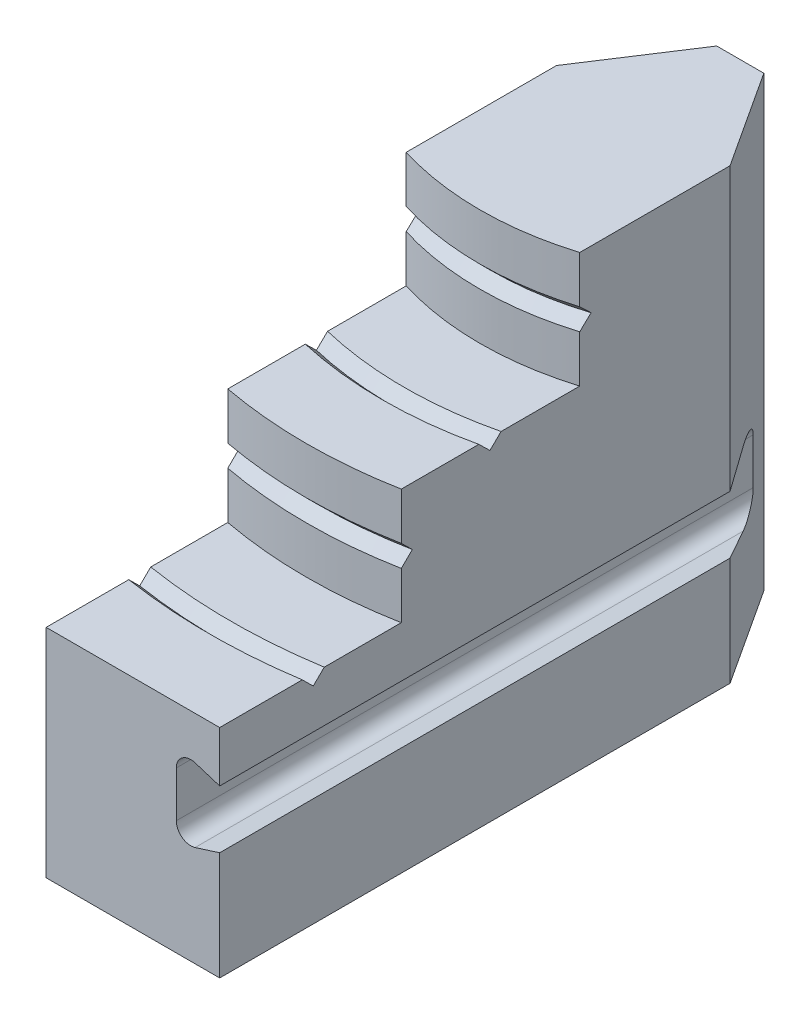
SolidWorks part; units mm, degrees
ref_plane "Front Plane" through (0, 0, 0) normal (0, 0, 1) x (1, 0, 0)
ref_plane "Top Plane" through (0, 0, 0) normal (0, 1, 0) x (1, 0, 0)
ref_plane "Right Plane" through (0, 0, 0) normal (1, 0, 0) x (0, 0, -1)
sketch "Sketch1" plane through (0, 0, 0) normal (0, 1, 0) x (1, 0, 0)
  line L0 (0, 0) -> (0, 89) construction
  line L1 (-12, 0) -> (12, 0)
  line L2 (-12, 0) -> (-12, 70.5832)
  line L3 (-3.2579, 84) -> (3.2579, 84)
  line L4 (12, 0) -> (12, 70.5832)
  line L5 (-3.2579, 84) -> (-12, 70.5832)
  line L6 (3.2579, 84) -> (12, 70.5832)
  line L7 (0, 89) -> (-3.2579, 84) construction
  line L8 (0, 89) -> (3.2579, 84) construction
  line L9 (-12, 70.5832) -> (-12, 84) construction
  line L10 (-12, 84) -> (-3.2579, 84) construction
  line L11 (12, 70.5832) -> (12, 84) construction
  line L12 (3.2579, 84) -> (12, 84) construction
  point P5 (0, 0)
  dimension "D1" = 24
  dimension "D2" = 89
  dimension "D3" = 84
  dimension "D4" = 33.087
extrude "Boss-Extrude1" add sketch "Sketch1" along normal blind 62
sketch "Sketch2" plane through (0, 0, 0) normal (1, 0, 0) x (0, 0, -1)
  line L0 (89, 0) -> (89, 113.7823) construction
  line L1 (89, 0) -> (84, 0) construction
  line L2 (0, 0) -> (89, 0) construction
  line L5 (48, 55.5) -> (49.5, 54)
  line L6 (-12, 30) -> (10.5, 30)
  line L7 (24, 30) -> (24, 36.5)
  line L8 (24, 46) -> (34.5, 46)
  line L9 (48, 46) -> (48, 52.5)
  line L10 (49.5, 54) -> (48, 52.5)
  line L13 (34.5, 46) -> (36, 44.5)
  line L15 (-12, 30) -> (-12, 70)
  line L16 (-12, 70) -> (48, 70)
  line L18 (0, 62) -> (0, 0) construction
  line L19 (0, 62) -> (70.5832, 62) construction
  line L20 (36, 44.5) -> (37.5, 46)
  line L21 (24, 39.5) -> (25.5, 38)
  line L22 (25.5, 38) -> (24, 36.5)
  line L23 (10.5, 30) -> (12, 28.5)
  line L24 (12, 28.5) -> (13.5, 30)
  line L25 (48, 52.5) -> (48, 55.5) construction
  line L26 (48, 55.5) -> (48, 70)
  line L27 (34.5, 46) -> (37.5, 46) construction
  line L28 (37.5, 46) -> (48, 46)
  line L29 (24, 36.5) -> (24, 39.5) construction
  line L30 (24, 39.5) -> (24, 46)
  line L31 (10.5, 30) -> (13.5, 30) construction
  line L32 (13.5, 30) -> (24, 30)
  dimension "D1" = 24
  dimension "D2" = 24
  dimension "D3" = 16
  dimension "D4" = 16
  dimension "D5" = 60
  dimension "D6" = 40
  dimension "D7" = 90
  dimension "D8" = 45
  dimension "D9" = 1.5
  dimension "D10" = 45
  dimension "D11" = 1.5
  dimension "D12" = 1.5
  dimension "D13" = 90
  dimension "D14" = 45
  dimension "D15" = 1.5
  dimension "D16" = 45
  dimension "D17" = 12
  dimension "D18" = 8
  dimension "D19" = 12
  dimension "D20" = 8
revolve "Cut-Revolve4" cut sketch "Sketch2" angle 360 about L0
sketch "Sketch3" plane through (0, 0, 0) normal (0, 0, 1) x (1, 0, 0)
  line L0 (12, 15) -> (8.6014, 13.9284)
  line L1 (12, 30) -> (12, 0) construction
  line L2 (6, 15.8359) -> (6, 22.1641)
  line L3 (8.6014, 24.0716) -> (12, 23)
  line L4 (12, 23) -> (12, 15)
  line L5 (-12, 0) -> (12, 0) construction
  line L6 (12, 19) -> (-15.2724, 19) construction
  arc A0 (6, 22.1641) -> (8.6014, 24.0716) centre (8, 22.1641) cw
  arc A1 (8.6014, 13.9284) -> (6, 15.8359) centre (8, 15.8359) cw
  dimension "D5" = 2
  dimension "D1" = 35
  dimension "D2" = 6
  dimension "D3" = 15
  dimension "D4" = 8
extrude "Cut-Extrude1" cut sketch "Sketch3" against normal through all
